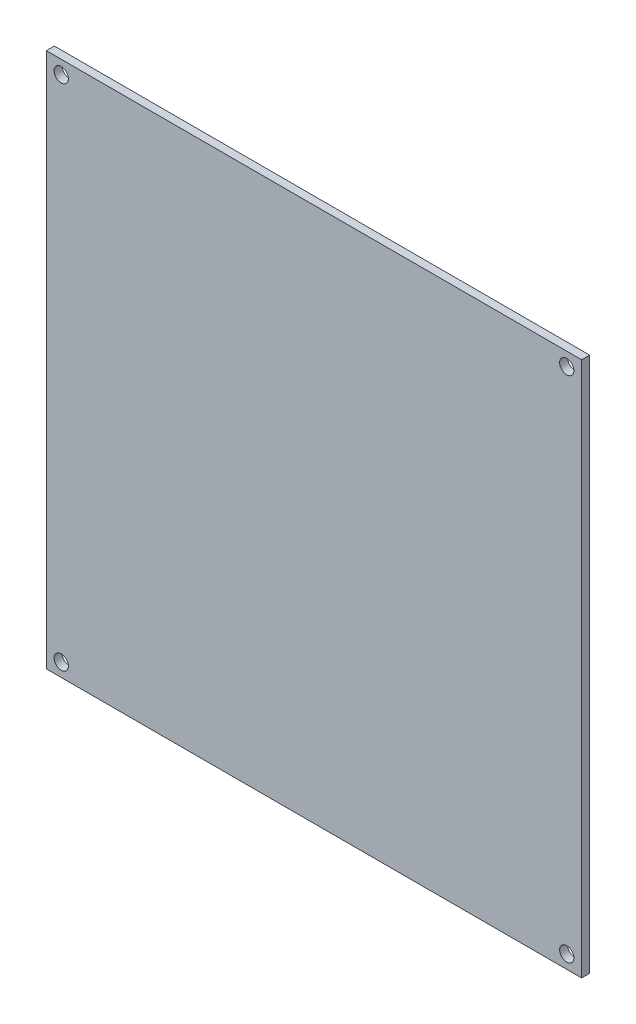
SolidWorks part; units mm, degrees
ref_plane "Front Plane" through (0, 0, 0) normal (0, 0, 1) x (1, 0, 0)
ref_plane "Top Plane" through (0, 0, 0) normal (0, 1, 0) x (1, 0, 0)
ref_plane "Right Plane" through (0, 0, 0) normal (1, 0, 0) x (0, 0, -1)
sketch "Sketch1" plane through (0, 0, 0) normal (0, 0, 1) x (1, 0, 0)
  line L1 (0, 0) -> (120, 0)
  line L2 (0, 0) -> (0, 120)
  line L3 (0, 120) -> (120, 120)
  line L4 (120, 0) -> (120, 120)
  circle A0 centre (3.35, 117) radius 1.6
  circle A1 centre (116.65, 117) radius 1.6
  circle A2 centre (116.65, 3) radius 1.6
  circle A3 centre (3.35, 3) radius 1.6
  point P13 (0, 0)
  point P14 (0, 0)
  point P15 (0, 0)
  point P16 (0, 0)
  point P17 (0, 0)
  point P18 (0, 0)
  dimension "D3" = 3.2
  dimension "D4" = 3.2
  dimension "D5" = 3.2
  dimension "D6" = 3.2
  dimension "D1" = 120
  dimension "D2" = 120
  dimension "D7" = 113.3
  dimension "D8" = 114
  dimension "D9" = 113.3
  dimension "D10" = 3.35
  dimension "D11" = 3
extrude "Boss-Extrude1" add sketch "Sketch1" along normal blind 1.8
